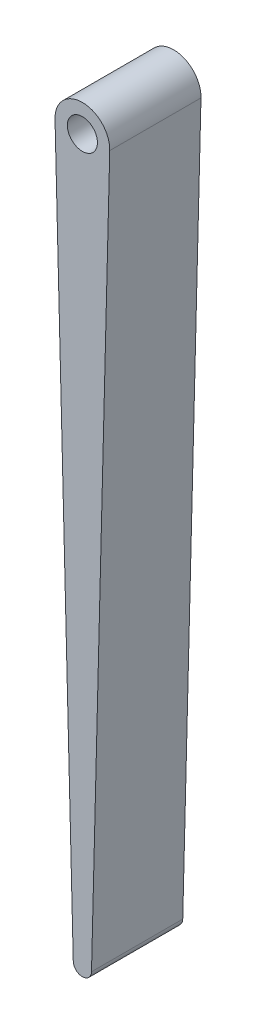
SolidWorks part; units mm, degrees
ref_plane "前视基准面" through (0, 0, 0) normal (0, 0, 1) x (1, 0, 0)
ref_plane "上视基准面" through (0, 0, 0) normal (0, 1, 0) x (1, 0, 0)
ref_plane "右视基准面" through (0, 0, 0) normal (1, 0, 0) x (0, 0, -1)
other "Configuration Table"
sketch "草图1" plane through (0, 0, 0) normal (0, 0, 1) x (1, 0, 0)
  line L0 (0, 8.6124) -> (0, -55.1151) construction
  line L1 (-5.9981, -0.1519) -> (-1.9994, -158.0506)
  line L2 (5.9981, -0.1519) -> (1.9994, -158.0506)
  circle A0 centre (0, 0) radius 3.3
  arc A1 (5.9981, -0.1519) -> (-5.9981, -0.1519) centre (0, 0) ccw
  arc A2 (-1.9994, -158.0506) -> (1.9994, -158.0506) centre (0, -158) ccw
  point P11 (0, -237)
  dimension "D1" = 6.6
  dimension "D2" = 12
  dimension "D4" = 2
  dimension "D3" = 160
extrude "凸台-拉伸1" add sketch "草图1" along normal blind 20
